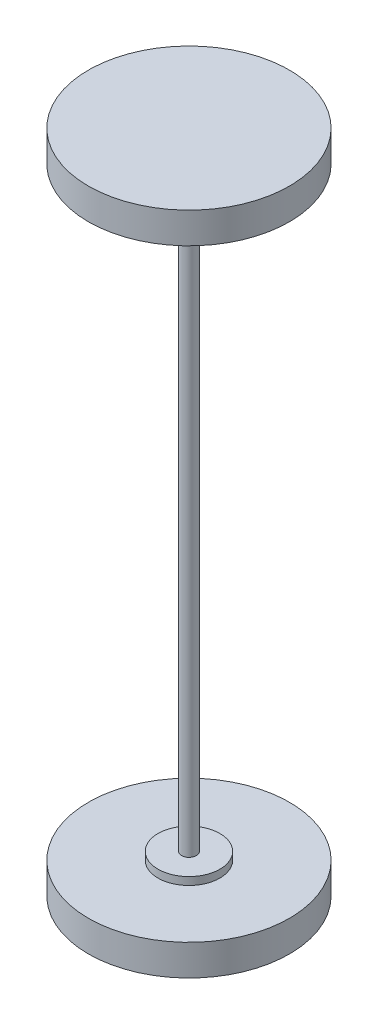
SolidWorks part; units mm, degrees
ref_plane "Front Plane" through (0, 0, 0) normal (0, 0, 1) x (1, 0, 0)
ref_plane "Top Plane" through (0, 0, 0) normal (0, 1, 0) x (1, 0, 0)
ref_plane "Right Plane" through (0, 0, 0) normal (1, 0, 0) x (0, 0, -1)
sketch "Sketch1" plane through (0, 0, 0) normal (0, 1, 0) x (1, 0, 0)
  circle A0 centre (0, 0) radius 32.5
  circle A1 centre (0, 0) radius 10
  circle A2 centre (0, 0) radius 2
  dimension "D1" = 65
  dimension "D2" = 20
extrude "Boss-Extrude1" add sketch "Sketch1" along normal mid plane 10 contours A0
sketch "Sketch2" plane through (0, 5, 0) normal (0, 1, 0) x (1, 0, 0)
  circle A0 centre (0, 0) radius 10
  dimension "D1" = 20
extrude "Boss-Extrude2" add sketch "Sketch2" along normal mid plane 5 contours A0
sketch "Sketch3" plane through (0, 7.5, 0) normal (0, 1, 0) x (1, 0, 0)
  circle A0 centre (0, 0) radius 2.4
extrude "Boss-Extrude3" add sketch "Sketch3" along normal blind 95
mirror "Mirror7" about plane through (0, 102.5, 0) normal (0, 1, 0) of bodies 103
